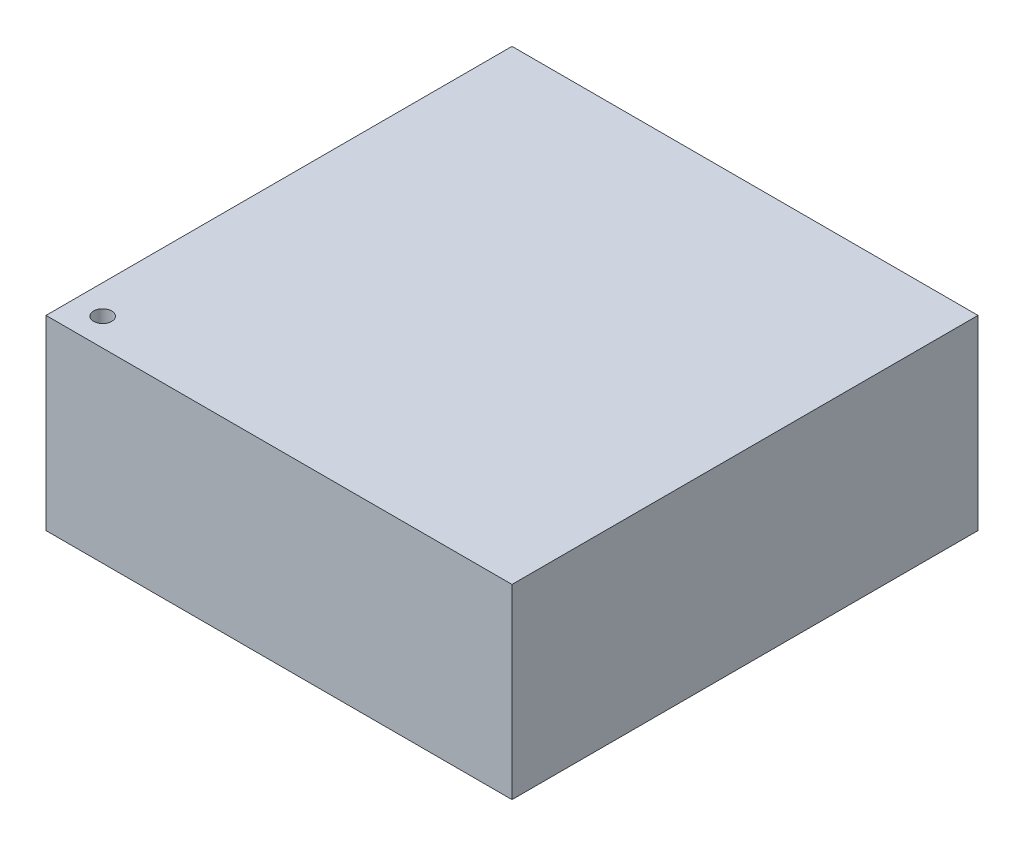
SolidWorks part; units mm, degrees
ref_plane "Front Plane" through (0, 0, 0) normal (0, 0, 1) x (1, 0, 0)
ref_plane "Top Plane" through (0, 0, 0) normal (0, 1, 0) x (1, 0, 0)
ref_plane "Right Plane" through (0, 0, 0) normal (1, 0, 0) x (0, 0, -1)
sketch "Sketch1" plane through (0, 0, 0) normal (0, 1, 0) x (1, 0, 0)
  line L1 (-65, 65) -> (65, 65)
  line L2 (-65, 65) -> (-65, -65)
  line L3 (-65, -65) -> (65, -65)
  line L4 (65, 65) -> (65, -65)
  line L5 (-65, 65) -> (65, -65) construction
  line L6 (-65, -65) -> (65, 65) construction
  point P0 (0, 0)
  dimension "D1" = 130
  dimension "D2" = 130
extrude "Boss-Extrude1" add sketch "Sketch1" along normal blind 52
sketch "Sketch2" plane through (0, 52, 0) normal (0, 1, 0) x (1, 0, 0)
  circle A0 centre (-56.9079, -57.2901) radius 2.5272
extrude "Cut-Extrude1" cut sketch "Sketch2" against normal blind 10
